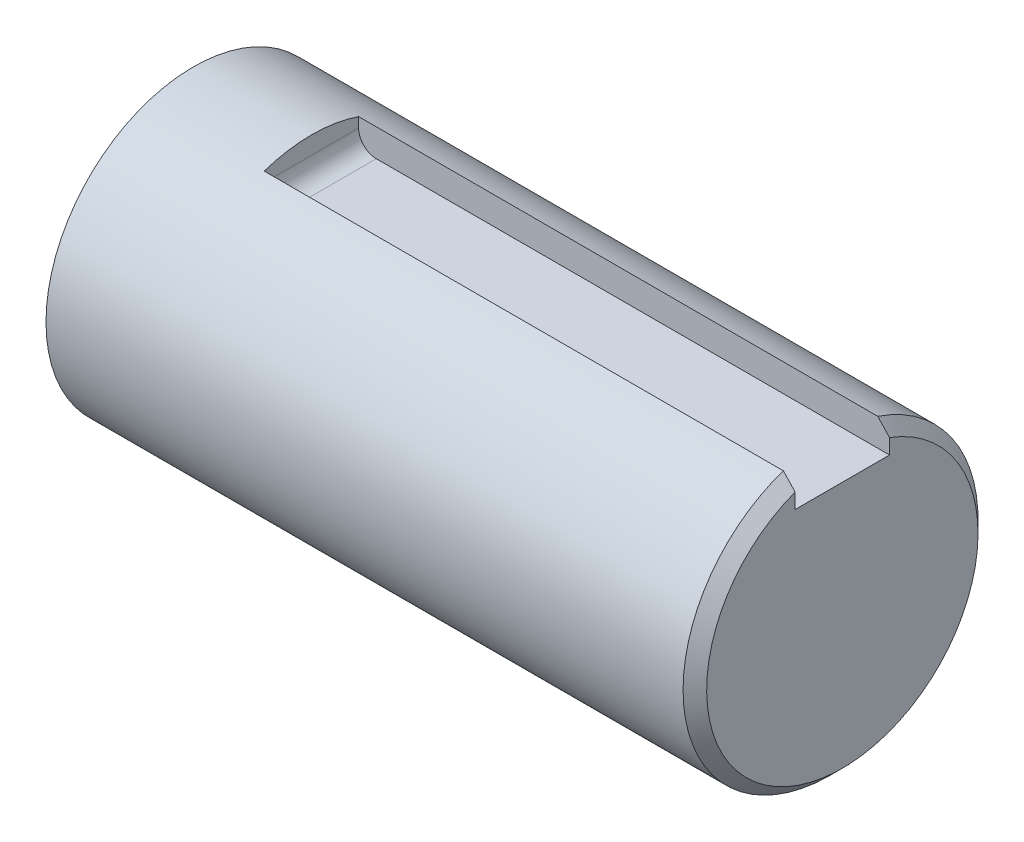
SolidWorks part; units mm, degrees
ref_plane "Front Plane" through (0, 0, 0) normal (0, 0, 1) x (1, 0, 0)
ref_plane "Top Plane" through (0, 0, 0) normal (0, 1, 0) x (1, 0, 0)
ref_plane "Right Plane" through (0, 0, 0) normal (1, 0, 0) x (0, 0, -1)
sketch "Sketch1" plane through (0, 0, 0) normal (0, 0, 1) x (1, 0, 0)
  line L0 (0, 0) -> (36443.4204, 0) construction
  line L1 (0, 0) -> (0, 36443.4204) construction
  line L2 (-55, 0) -> (55, 0)
  line L3 (-55, 25) -> (55, 25)
  line L4 (-55, 25) -> (-55, 0)
  line L5 (55, 25) -> (55, 0)
  point P7 (0, 0)
  dimension "D1" = 50
  dimension "D2" = 110
revolve "Revolve1" add sketch "Sketch1" angle 360 about L2
sketch "Sketch2" plane through (55, 0, 0) normal (1, 0, 0) x (0, 0, -1)
  line L0 (0, 0) -> (17.058, 0) construction
  line L1 (-8, 30.869) -> (-8, 19)
  line L2 (-8, 19) -> (8, 19)
  line L3 (8, 19) -> (8, 30.869)
  line L4 (-8, 30.869) -> (8, 30.869)
  circle A0 centre (0, 0) radius 25 construction
  point P5 (0, 19)
  dimension "D1" = 16
  dimension "D2" = 44
extrude "Cut-Extrude1" cut sketch "Sketch2" against normal blind 90
chamfer "Chamfer1" distance 2 angle 45 1 edges at (55, -25, 0)
fillet "Fillet1" radius 3 1 edges at (-35, 19, 0)
